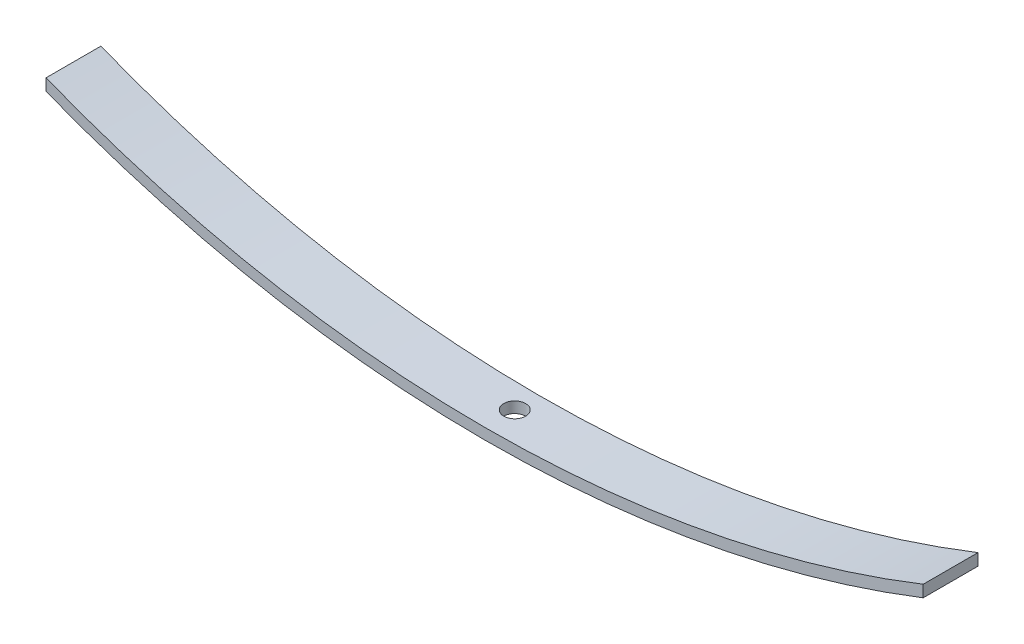
SolidWorks part; units mm, degrees
ref_plane "Front Plane" through (0, 0, 0) normal (0, 0, 1) x (1, 0, 0)
ref_plane "Top Plane" through (0, 0, 0) normal (0, 1, 0) x (1, 0, 0)
ref_plane "Right Plane" through (0, 0, 0) normal (1, 0, 0) x (0, 0, -1)
sketch "Sketch1" plane through (0, 0, 0) normal (0, 0, 1) x (1, 0, 0)
  line L0 (-400, -1024.6951) -> (-400, -1013.9527)
  line L1 (0, 0) -> (0, -3000.7365)
  line L2 (400, -1024.6951) -> (400, -1013.9527)
  arc A0 (-400, -1024.6951) -> (400, -1024.6951) centre (0, 0) ccw
  arc A1 (-400, -1013.9527) -> (400, -1013.9527) centre (0, 0) ccw
  point P7 (-400, -1019.3239)
  dimension "D1" = 2200
  dimension "D2" = 2180
  dimension "D3" = 400
extrude "Boss-Extrude1" add sketch "Sketch1" along normal blind 50 contours A0 L2 A1 L0
sketch "Sketch3" plane through (0, 0, 0) normal (0, 1, 0) x (1, 0, 0)
  line L0 (0, 0) -> (0, -53.543) construction
  line L1 (400, 0) -> (-400, 0) construction
  circle A0 centre (0, -22.5) radius 10
  dimension "D1" = 20
  dimension "D2" = 22.5
extrude "Cut-Extrude1" cut sketch "Sketch3" against normal through all
